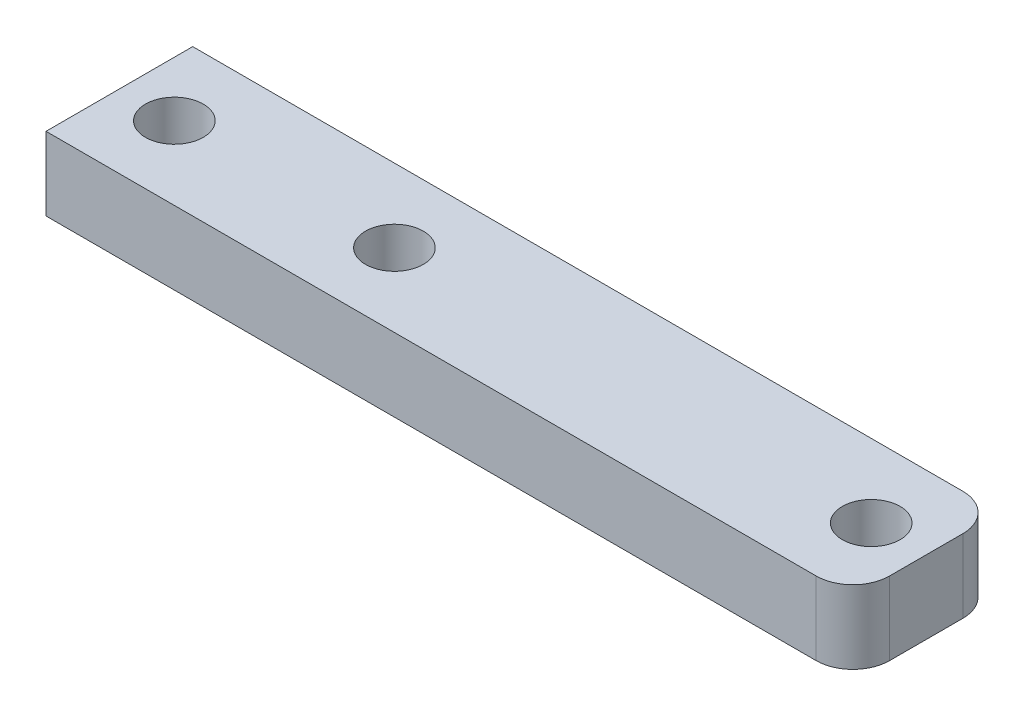
SolidWorks part; units mm, degrees
material "CRS"
ref_plane "Z" through (0, 0, 0) normal (0, 0, 1) x (1, 0, 0)
ref_plane "Y" through (0, 0, 0) normal (0, 1, 0) x (1, 0, 0)
ref_plane "X" through (0, 0, 0) normal (1, 0, 0) x (0, 0, -1)
sketch "Sketch1" plane through (0, 0, 0) normal (0, 1, 0) x (1, 0, 0)
  line L1 (0, 6.35) -> (69.85, 6.35)
  line L2 (0, 6.35) -> (0, -6.35)
  line L3 (0, -6.35) -> (69.85, -6.35)
  line L4 (69.85, 6.35) -> (69.85, -6.35)
  dimension "D1" = 69.85
  dimension "D2" = 12.7
extrude "Boss-Extrude1" add sketch "Sketch1" along normal blind 6.35
hole_wizard "M6x1.0 Tapped Hole1" positions "Sketch3" profile "Sketch2" tap size "M6x1.0" standard "ANSI Metric" end condition through all
sketch "Sketch3" plane through (0, 6.35, 0) normal (0, 1, 0) x (1, 0, 0)
  line L0 (0, 6.35) -> (0, -6.35) construction
  line L1 (69.85, -6.35) -> (69.85, 6.35) construction
  point P0 (4.7625, 0)
  point P2 (23.8125, 0)
  point P18 (65.0875, 0)
  dimension "D1" = 4.7625
  dimension "D2" = 19.05
  dimension "D3" = 4.7625
sketch "Sketch2" plane through (4.7625, 6.35, 0) normal (1, 0, 0) x (0, 0, 1)
  line L0 (0, 0) -> (0, 6.35)
  line L1 (0, 6.35) -> (2.5, 6.35)
  line L2 (2.5, 6.35) -> (2.5, 0)
  line L5 (2.5, 0) -> (0, 0)
  line L11 (0, -6.35) -> (0, 107.95) construction
  dimension "Thru Tap Drill Dia." = 5
  dimension "Thru Tap Drill Depth" = 6.35
cosmetic thread "Hole Thread1"
cosmetic thread "Hole Thread2"
cosmetic thread "Hole Thread4"
fillet "Fillet1" radius 3.175 2 edges at (69.85, 3.175, -6.35) (69.85, 3.175, 6.35)
sketch "Bend Location" plane through (0, 6.35, 0) normal (0, 1, 0) x (1, 0, 0)
  line L0 (0, -3.4925) -> (0, 3.4925) construction
  point P0 (38.1, 0)
  point P1 (50.8, 0)
  dimension "D1" = 38.1
  dimension "D2" = 12.7
other "Flex1-Suppress for Straight" [suppressed] parameters "D0"=20
